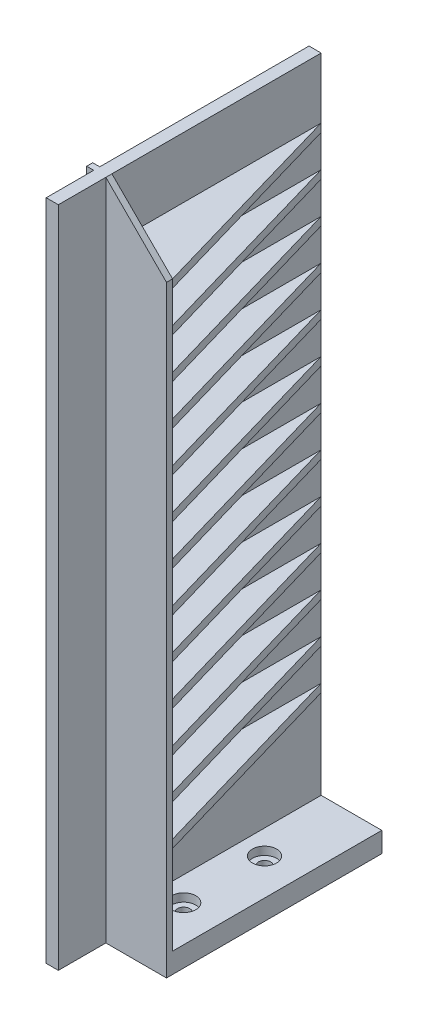
SolidWorks part; units mm, degrees
ref_plane "前视基准面" through (0, 0, 0) normal (0, 0, 1) x (1, 0, 0)
ref_plane "上视基准面" through (0, 0, 0) normal (0, 1, 0) x (1, 0, 0)
ref_plane "右视基准面" through (0, 0, 0) normal (1, 0, 0) x (0, 0, -1)
other "Configuration Table"
sketch "草图1" plane through (0, 0, 0) normal (0, 1, 0) x (1, 0, 0)
  line L0 (0, 0) -> (0, -65)
  line L1 (0, 0) -> (18, 0)
  line L2 (18, 0) -> (18, -50)
  line L3 (0, -65) -> (3, -65)
  line L4 (3, -65) -> (3, -50)
  line L5 (3, -50) -> (18, -50)
extrude "凸台-拉伸1" add sketch "草图1" along normal blind 164
sketch "草图3" plane through (0, 164, 0) normal (0, 1, 0) x (1, 0, 0)
  circle A0 centre (9, -20) radius 1.5
  circle A1 centre (9, -40) radius 1.5
extrude "切除-拉伸1" cut sketch "草图3" against normal blind 164
sketch "草图4" plane through (0, 164, 0) normal (0, 1, 0) x (1, 0, 0)
  line L0 (0, -65) -> (0, -53.5)
  line L1 (0, 0) -> (0, -65) construction
  line L3 (0, -53.5) -> (-2, -53.5)
  line L4 (0, -53.5) -> (0, -51.5)
  line L5 (0, -51.5) -> (-2, -51.5)
  line L6 (-2, -53.5) -> (-2, -51.5)
  line M9 (0, 0) -> (0, -65)
extrude "凸台-拉伸2" add sketch "草图4" against normal blind 164 contours L6 L3 L5 M9
sketch "草图5" plane through (0, 0, 0) normal (0, -1, 0) x (1, 0, 0)
  line L0 (-2, 53.25) -> (0, 53.25)
  line L1 (-2, 53.5) -> (0, 53.5)
  line L2 (-2, 53.5) -> (-2, 53.25)
  line L4 (0, 53.5) -> (0, 53.25)
  line L5 (-2, 51.5) -> (0, 51.5)
  line L6 (-2, 51.5) -> (-2, 51.75)
  line L7 (-2, 51.75) -> (0, 51.75)
  line L8 (0, 51.5) -> (0, 51.75)
  line L9 (-2, 53.25) -> (-1.75, 53.25)
  line L10 (-2, 53.25) -> (-2, 51.75)
  line L11 (-2, 51.75) -> (-1.75, 51.75)
  line L12 (-1.75, 53.25) -> (-1.75, 51.75)
  line M17 (0, 53.5) -> (-2, 53.5)
  line M18 (-2, 53.5) -> (-2, 51.5)
  line M19 (-2, 51.5) -> (0, 51.5)
extrude "切除-拉伸2" cut sketch "草图5" against normal blind 164 contours L8 L7 M19 M18 | L12 L0 L7 M18 | L4 L0 M17 M18
sketch "草图6" plane through (0, 164, 0) normal (0, 1, 0) x (1, 0, 0)
  line L1 (3, -50) -> (18, -50)
  line L2 (3, -50) -> (3, 0)
  line L3 (3, 0) -> (18, 0)
  line L4 (18, -50) -> (18, 0)
extrude "切除-拉伸3" cut sketch "草图6" against normal blind 159
sketch "草图7" plane through (0, 164, 0) normal (0, 1, 0) x (1, 0, 0)
  line L0 (3, -65) -> (3, 0) construction
  line L1 (-1.75, -53.25) -> (0, -53.25)
  line L2 (-1.75, -53.25) -> (-1.75, -51.75)
  line L3 (-1.75, -51.75) -> (0, -51.75)
  line L4 (0, -53.25) -> (0, -51.75)
  line L5 (0, -53.25) -> (3, -53.25)
  line L6 (0, -53.25) -> (0, -51.75)
  line L7 (0, -51.75) -> (3, -51.75)
  line L8 (3, -53.25) -> (3, -51.75)
  line L10 (3, -53.25) -> (18, -53.25)
  line L11 (3, -53.25) -> (3, -51.75)
  line L12 (3, -51.75) -> (18, -51.75)
  line L13 (18, -53.25) -> (18, -51.75)
  line M1 (3, -65) -> (3, 0)
extrude "凸台-拉伸3" add sketch "草图7" against normal blind 159 contours L10 L13 L12 M1
sketch "草图8" plane through (3, 0, 0) normal (1, 0, 0) x (0, 0, -1)
  line L1 (-53.25, 5) -> (-50, 5)
  line L2 (-53.25, 5) -> (-53.25, 0)
  line L3 (-53.25, 0) -> (-50, 0)
  line L4 (-50, 5) -> (-50, 0)
extrude "凸台-拉伸4" add sketch "草图8" along normal blind 15
sketch "草图9" plane through (0, 0, 53.25) normal (0, 0, 1) x (1, 0, 0)
  line L1 (3, 164) -> (18, 164)
  line L2 (18, 164) -> (18, 149)
  line L3 (18, 149) -> (3, 164)
extrude "切除-拉伸4" cut sketch "草图9" against normal blind 15
sketch "草图10" plane through (0, 5, 0) normal (0, 1, 0) x (1, 0, 0)
  circle A0 centre (9, -20) radius 3
  circle A1 centre (9, -40) radius 3
extrude "切除-拉伸5" cut sketch "草图10" against normal blind 2
sketch "草图11" plane through (3, 0, 0) normal (1, 0, 0) x (0, 0, -1)
  line L0 (0, 5) -> (0, 164) construction
  line L1 (-51.75, 149) -> (0, 149)
  line L2 (-51.75, 149) -> (-51.75, 147)
  line L3 (-51.75, 147) -> (0, 147)
  line L4 (0, 149) -> (0, 147)
  line L5 (0, 139) -> (0, 137)
  line L6 (-51.75, 139) -> (-51.75, 137)
  line L7 (-51.75, 139) -> (0, 139)
  line L8 (-51.75, 137) -> (0, 137)
  line L9 (0, 129) -> (0, 127)
  line L10 (-51.75, 129) -> (-51.75, 127)
  line L11 (-51.75, 129) -> (0, 129)
  line L12 (-51.75, 127) -> (0, 127)
  line L13 (0, 119) -> (0, 117)
  line L14 (-51.75, 119) -> (-51.75, 117)
  line L15 (-51.75, 119) -> (0, 119)
  line L16 (-51.75, 117) -> (0, 117)
  line L17 (0, 109) -> (0, 107)
  line L18 (-51.75, 109) -> (-51.75, 107)
  line L19 (-51.75, 109) -> (0, 109)
  line L20 (-51.75, 107) -> (0, 107)
  line L21 (0, 99) -> (0, 97)
  line L22 (-51.75, 99) -> (-51.75, 97)
  line L23 (-51.75, 99) -> (0, 99)
  line L24 (-51.75, 97) -> (0, 97)
  line L25 (0, 89) -> (0, 87)
  line L26 (-51.75, 89) -> (-51.75, 87)
  line L27 (-51.75, 89) -> (0, 89)
  line L28 (-51.75, 87) -> (0, 87)
  line L29 (0, 79) -> (0, 77)
  line L30 (-51.75, 79) -> (-51.75, 77)
  line L31 (-51.75, 79) -> (0, 79)
  line L32 (-51.75, 77) -> (0, 77)
  line L33 (0, 69) -> (0, 67)
  line L34 (-51.75, 69) -> (-51.75, 67)
  line L35 (-51.75, 69) -> (0, 69)
  line L36 (-51.75, 67) -> (0, 67)
  line L37 (0, 59) -> (0, 57)
  line L38 (-51.75, 59) -> (-51.75, 57)
  line L39 (-51.75, 59) -> (0, 59)
  line L40 (-51.75, 57) -> (0, 57)
  line L41 (0, 49) -> (0, 47)
  line L42 (-51.75, 49) -> (-51.75, 47)
  line L43 (-51.75, 49) -> (0, 49)
  line L44 (-51.75, 47) -> (0, 47)
  line L45 (0, 39) -> (0, 37)
  line L46 (-51.75, 39) -> (-51.75, 37)
  line L47 (-51.75, 39) -> (0, 39)
  line L48 (-51.75, 37) -> (0, 37)
  line L49 (0, 29) -> (0, 27)
  line L50 (-51.75, 29) -> (-51.75, 27)
  line L51 (-51.75, 29) -> (0, 29)
  line L52 (-51.75, 27) -> (0, 27)
  dimension "D1" = 13
extrude "凸台-拉伸5" add sketch "草图11" along normal blind 15
sketch "草图12" plane through (0, 149, 0) normal (0, 1, 0) x (1, 0, 0)
  line L0 (3, 0) -> (18, -51.75)
  line L1 (18, -51.75) -> (18, 0)
  line L2 (18, 0) -> (3, 0)
extrude "切除-拉伸6" cut sketch "草图12" against normal blind 130
